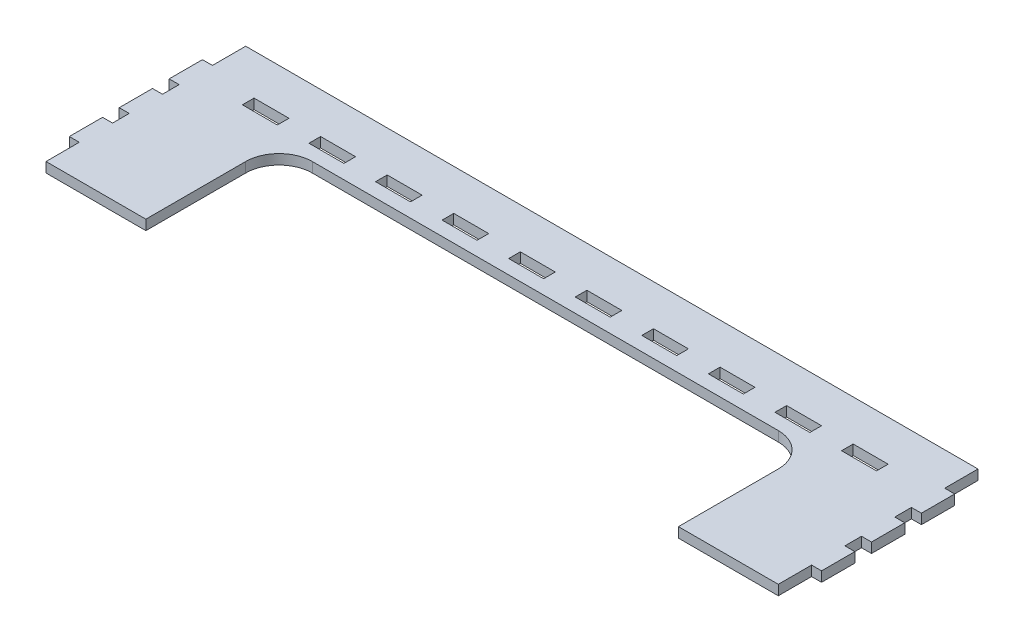
SolidWorks part; units mm, degrees
ref_plane "Спереди" through (0, 0, 0) normal (0, 0, 1) x (1, 0, 0)
ref_plane "Сверху" through (0, 0, 0) normal (0, 1, 0) x (1, 0, 0)
ref_plane "Справа" through (0, 0, 0) normal (1, 0, 0) x (0, 0, -1)
sketch "Эскиз1" plane through (0, 0, 0) normal (0, 1, 0) x (1, 0, 0)
  line L0 (-135, -31.7889) -> (-138, -31.7889)
  line L1 (45, -16.7889) -> (-95, -16.7889)
  line L2 (85, -31.7889) -> (85, -36.7889)
  line L3 (75, 3.2111) -> (-125, 3.2111)
  line L4 (-138, -31.7889) -> (-138, -21.7889)
  line L5 (-135, -56.7889) -> (-105, -56.7889)
  line L6 (-105, -56.7889) -> (-105, -26.7889)
  line L7 (-25, -16.7889) -> (-25, 56.3847) construction
  line L8 (85, -56.7889) -> (55, -56.7889)
  line L9 (55, -56.7889) -> (55, -26.7889)
  line L10 (85, -16.7889) -> (85, -21.7889)
  line L11 (-138, -21.7889) -> (-135, -21.7889)
  line L12 (-135, 3.2111) -> (-125, 3.2111)
  line L13 (85, 3.2111) -> (85, -6.7889)
  line L14 (85, 3.2111) -> (75, 3.2111)
  line L15 (-135, -46.7889) -> (-138, -46.7889)
  line L16 (-138, -46.7889) -> (-138, -36.7889)
  line L17 (-138, -36.7889) -> (-135, -36.7889)
  line L18 (-135, -46.7889) -> (-135, -56.7889)
  line L19 (-135, -16.7889) -> (-138, -16.7889)
  line L20 (-138, -16.7889) -> (-138, -6.7889)
  line L21 (-138, -6.7889) -> (-135, -6.7889)
  line L22 (-135, 3.2111) -> (-135, -6.7889)
  line L23 (-135, -16.7889) -> (-135, -21.7889)
  line L24 (-135, -31.7889) -> (-135, -36.7889)
  line L25 (88, -6.7889) -> (85, -6.7889)
  line L26 (88, -16.7889) -> (88, -6.7889)
  line L27 (85, -16.7889) -> (88, -16.7889)
  line L28 (85, -46.7889) -> (85, -56.7889)
  line L29 (88, -36.7889) -> (85, -36.7889)
  line L30 (88, -46.7889) -> (88, -36.7889)
  line L31 (85, -46.7889) -> (88, -46.7889)
  line L32 (88, -21.7889) -> (85, -21.7889)
  line L33 (88, -31.7889) -> (88, -21.7889)
  line L34 (85, -31.7889) -> (88, -31.7889)
  arc A2 (55, -26.7889) -> (45, -16.7889) centre (45, -26.7889) ccw
  arc A3 (-95, -16.7889) -> (-105, -26.7889) centre (-95, -26.7889) ccw
  point P0 (0, 0)
  point P16 (85, 3.2111)
  point P19 (-135, 3.2111)
  point P22 (55, -16.7889)
  point P25 (-105, -16.7889)
  dimension "D5" = 3
  dimension "D6" = 10
  dimension "D1" = 220
  dimension "D2" = 60
  dimension "D3" = 3
  dimension "D4" = 30
  dimension "D7" = 10
  dimension "D8" = 10
extrude "Бобышка-Вытянуть1" add sketch "Эскиз1" along normal blind 3
sketch "Эскиз2" plane through (0, 0, 0) normal (0, 1, 0) x (1, 0, 0)
  line L0 (-95, -16.7889) -> (45, -16.7889) construction
  line L1 (-105, -10.7889) -> (-44.1885, -10.7889) construction
  line L3 (-120.25, -12.5389) -> (-109.75, -12.5389)
  line L4 (-120.25, -12.5389) -> (-120.25, -9.0389)
  line L5 (-120.25, -9.0389) -> (-109.75, -9.0389)
  line L6 (-109.75, -12.5389) -> (-109.75, -9.0389)
  line L7 (-120.25, -12.5389) -> (-109.75, -9.0389) construction
  line L8 (-120.25, -9.0389) -> (-109.75, -12.5389) construction
  line L10 (-100.25, -9.0389) -> (-89.75, -9.0389)
  line L11 (-100.25, -12.5389) -> (-100.25, -9.0389)
  line L12 (-100.25, -12.5389) -> (-89.75, -12.5389)
  line L13 (-89.75, -12.5389) -> (-89.75, -9.0389)
  line L14 (-80.25, -9.0389) -> (-69.75, -9.0389)
  line L15 (-80.25, -12.5389) -> (-80.25, -9.0389)
  line L16 (-80.25, -12.5389) -> (-69.75, -12.5389)
  line L17 (-69.75, -12.5389) -> (-69.75, -9.0389)
  line L18 (-60.25, -9.0389) -> (-49.75, -9.0389)
  line L19 (-60.25, -12.5389) -> (-60.25, -9.0389)
  line L20 (-60.25, -12.5389) -> (-49.75, -12.5389)
  line L21 (-49.75, -12.5389) -> (-49.75, -9.0389)
  line L22 (-40.25, -9.0389) -> (-29.75, -9.0389)
  line L23 (-40.25, -12.5389) -> (-40.25, -9.0389)
  line L24 (-40.25, -12.5389) -> (-29.75, -12.5389)
  line L25 (-29.75, -12.5389) -> (-29.75, -9.0389)
  line L26 (-20.25, -9.0389) -> (-9.75, -9.0389)
  line L27 (-20.25, -12.5389) -> (-20.25, -9.0389)
  line L28 (-20.25, -12.5389) -> (-9.75, -12.5389)
  line L29 (-9.75, -12.5389) -> (-9.75, -9.0389)
  line L30 (-0.25, -9.0389) -> (10.25, -9.0389)
  line L31 (-0.25, -12.5389) -> (-0.25, -9.0389)
  line L32 (-0.25, -12.5389) -> (10.25, -12.5389)
  line L33 (10.25, -12.5389) -> (10.25, -9.0389)
  line L34 (19.75, -9.0389) -> (30.25, -9.0389)
  line L35 (19.75, -12.5389) -> (19.75, -9.0389)
  line L36 (19.75, -12.5389) -> (30.25, -12.5389)
  line L37 (30.25, -12.5389) -> (30.25, -9.0389)
  line L38 (39.75, -9.0389) -> (50.25, -9.0389)
  line L39 (39.75, -12.5389) -> (39.75, -9.0389)
  line L40 (39.75, -12.5389) -> (50.25, -12.5389)
  line L41 (50.25, -12.5389) -> (50.25, -9.0389)
  line L42 (59.75, -9.0389) -> (70.25, -9.0389)
  line L43 (59.75, -12.5389) -> (59.75, -9.0389)
  line L44 (59.75, -12.5389) -> (70.25, -12.5389)
  line L45 (70.25, -12.5389) -> (70.25, -9.0389)
  point P0 (-105, -10.7889)
  point P2 (0, 0)
  point P4 (-115, -10.7889)
  dimension "D1" = 14.75
  dimension "D2" = 3.5
  dimension "D3" = 10.5
  dimension "D6" = 6
  dimension "D5" = 10
extrude "Вырез-Вытянуть1" cut sketch "Эскиз2" along normal through all
